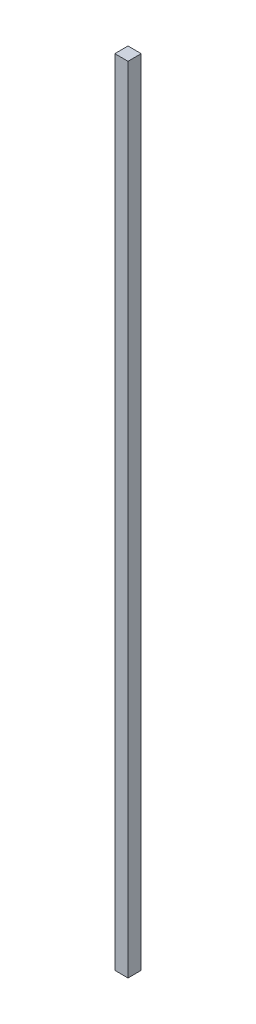
SolidWorks part; units mm, degrees
ref_plane "Спереди" through (0, 0, 0) normal (0, 0, 1) x (1, 0, 0)
ref_plane "Сверху" through (0, 0, 0) normal (0, 1, 0) x (1, 0, 0)
ref_plane "Справа" through (0, 0, 0) normal (1, 0, 0) x (0, 0, -1)
other "Configuration Table"
sketch "Эскиз1" plane through (0, 0, 0) normal (0, 1, 0) x (1, 0, 0)
  line L1 (25, 25) -> (-25, 25)
  line L2 (25, 25) -> (25, -25)
  line L3 (25, -25) -> (-25, -25)
  line L4 (-25, 25) -> (-25, -25)
  line L5 (25, 25) -> (-25, -25) construction
  line L6 (25, -25) -> (-25, 25) construction
  point P0 (0, 0)
extrude "Бобышка-Вытянуть1" add sketch "Эскиз1" along normal blind 3000
